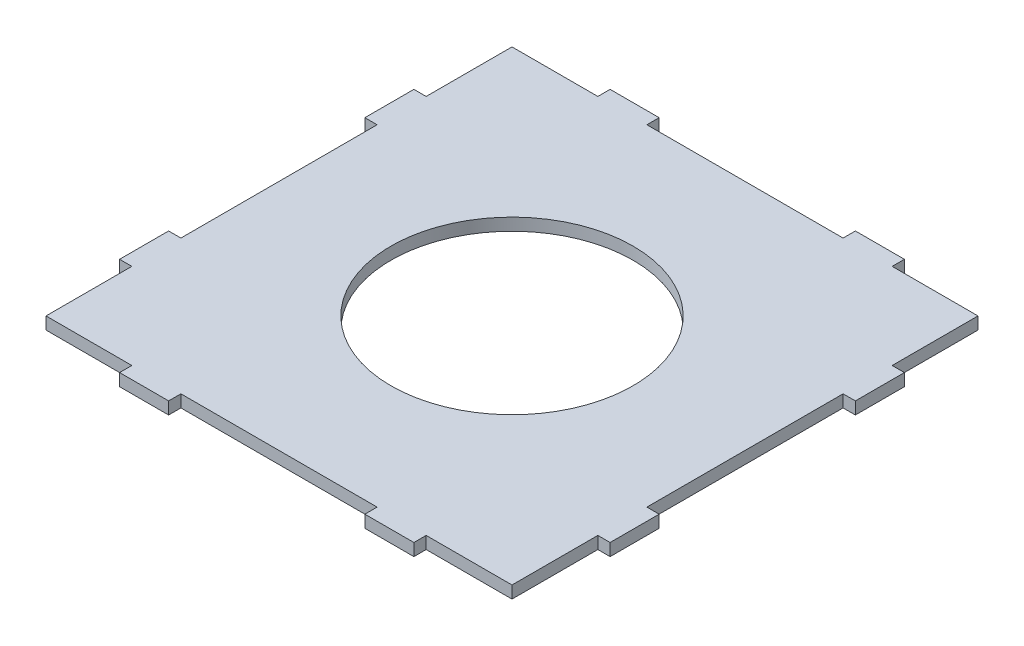
SolidWorks part; units mm, degrees
ref_plane "Front Plane" through (0, 0, 0) normal (0, 0, 1) x (1, 0, 0)
ref_plane "Top Plane" through (0, 0, 0) normal (0, 1, 0) x (1, 0, 0)
ref_plane "Right Plane" through (0, 0, 0) normal (1, 0, 0) x (0, 0, -1)
sketch "Sketch1" plane through (0, 0, 0) normal (0, 1, 0) x (1, 0, 0)
  line L0 (-83.3654, 80.7881) -> (-48.3654, 80.7881)
  line L1 (106.6346, -109.2119) -> (71.6346, -109.2119)
  line L2 (106.6346, -109.2119) -> (106.6346, -74.2119)
  line L3 (106.6346, 80.7881) -> (71.6346, 80.7881)
  line L4 (-83.3654, -74.2119) -> (-83.3654, -109.2119)
  line L5 (-83.3654, 45.7881) -> (-83.3654, 80.7881)
  line L6 (-88.3654, 45.7881) -> (-83.3654, 45.7881)
  line L7 (-88.3654, 45.7881) -> (-88.3654, 25.7881)
  line L8 (-88.3654, 25.7881) -> (-83.3654, 25.7881)
  line L9 (-48.3654, -109.2119) -> (-83.3654, -109.2119)
  line L10 (-88.3654, -54.2119) -> (-83.3654, -54.2119)
  line L11 (-88.3654, -54.2119) -> (-88.3654, -74.2119)
  line L12 (-88.3654, -74.2119) -> (-83.3654, -74.2119)
  line L13 (-83.3654, -54.2119) -> (-83.3654, 25.7881)
  line L14 (51.6346, -109.2119) -> (-28.3654, -109.2119)
  line L15 (-48.3654, -114.2119) -> (-28.3654, -114.2119)
  line L16 (106.6346, -54.2119) -> (106.6346, 25.7881)
  line L17 (51.6346, -114.2119) -> (71.6346, -114.2119)
  line L18 (106.6346, 45.7881) -> (106.6346, 80.7881)
  line L19 (51.6346, 80.7881) -> (-28.3654, 80.7881)
  line L20 (111.6346, -74.2119) -> (111.6346, -54.2119)
  line L21 (106.6346, -109.2119) -> (46.5305, -49.1078)
  line L22 (111.6346, 25.7881) -> (111.6346, 45.7881)
  line L25 (71.6346, 85.7881) -> (51.6346, 85.7881)
  line L27 (-28.3654, 85.7881) -> (-48.3654, 85.7881)
  line L30 (-48.3654, 85.7881) -> (-48.3654, 80.7881)
  line L31 (-28.3654, 85.7881) -> (-28.3654, 80.7881)
  line L32 (51.6346, 85.7881) -> (51.6346, 80.7881)
  line L33 (71.6346, 85.7881) -> (71.6346, 80.7881)
  line L34 (111.6346, 45.7881) -> (106.6346, 45.7881)
  line L35 (111.6346, 25.7881) -> (106.6346, 25.7881)
  line L36 (111.6346, -54.2119) -> (106.6346, -54.2119)
  line L37 (111.6346, -74.2119) -> (106.6346, -74.2119)
  line L38 (71.6346, -114.2119) -> (71.6346, -109.2119)
  line L39 (51.6346, -114.2119) -> (51.6346, -109.2119)
  line L40 (-28.3654, -114.2119) -> (-28.3654, -109.2119)
  line L41 (-48.3654, -114.2119) -> (-48.3654, -109.2119)
  circle A0 centre (11.6346, -14.2119) radius 49.3503
  dimension "D1" = 190
  dimension "D2" = 190
  dimension "D3" = 35
  dimension "D4" = 80
  dimension "D5" = 35
  dimension "D6" = 20
  dimension "D7" = 20
  dimension "D8" = 5
  dimension "D9" = 5
  dimension "D10" = 35
  dimension "D11" = 20
  dimension "D12" = 80
  dimension "D13" = 20
  dimension "D14" = 35
  dimension "D15" = 200
  dimension "D16" = 200
extrude "Boss-Extrude2" add sketch "Sketch1" along normal blind 5
